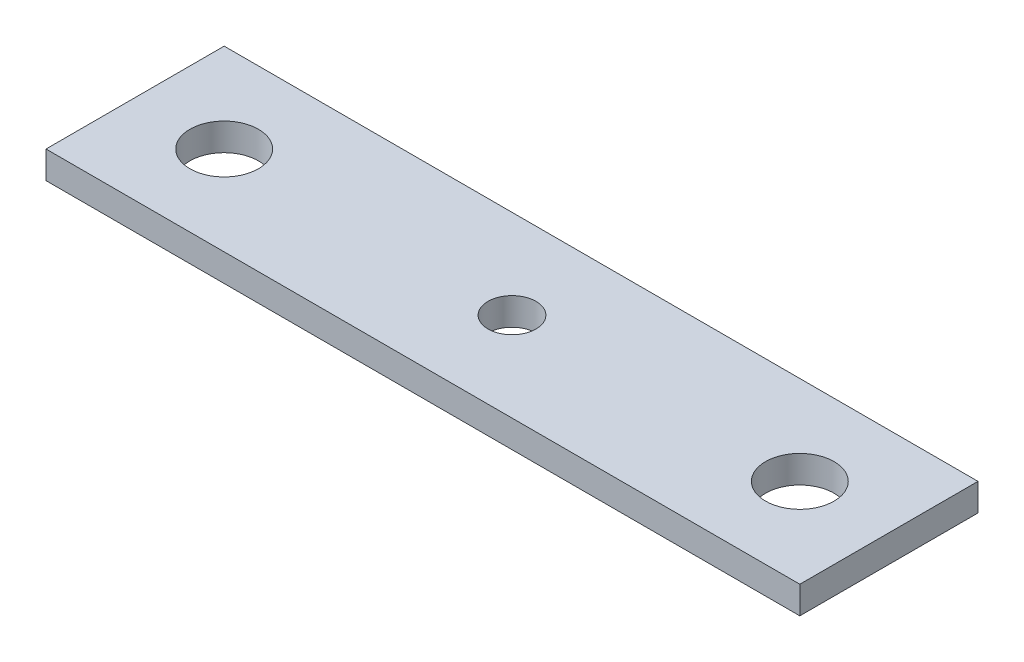
SolidWorks part; units mm, degrees
ref_plane "Front Plane" through (0, 0, 0) normal (0, 0, 1) x (1, 0, 0)
ref_plane "Top Plane" through (0, 0, 0) normal (0, 1, 0) x (1, 0, 0)
ref_plane "Right Plane" through (0, 0, 0) normal (1, 0, 0) x (0, 0, -1)
sketch "Sketch1" plane through (0, 0, 0) normal (0, 1, 0) x (1, 0, 0)
  line L0 (-55, 0) -> (55, 0) construction
  line L1 (-27.5, 6.5) -> (27.5, 6.5)
  line L2 (-27.5, 6.5) -> (-27.5, -6.5)
  line L3 (-27.5, -6.5) -> (27.5, -6.5)
  line L4 (27.5, 6.5) -> (27.5, -6.5)
  line L5 (-27.5, 6.5) -> (27.5, -6.5) construction
  line L6 (-27.5, -6.5) -> (27.5, 6.5) construction
  circle A0 centre (-21, 0) radius 2.5
  circle A1 centre (21, 0) radius 2.5
  circle A2 centre (0, 0) radius 1.75
  point P0 (0, 0)
  point P14 (0, 0)
  dimension "D3" = 5
  dimension "D5" = 5
  dimension "D7" = 3.5
  dimension "D1" = 55
  dimension "D2" = 13
  dimension "D4" = 6.5
  dimension "D6" = 42
extrude "Boss-Extrude1" add sketch "Sketch1" along normal blind 2
